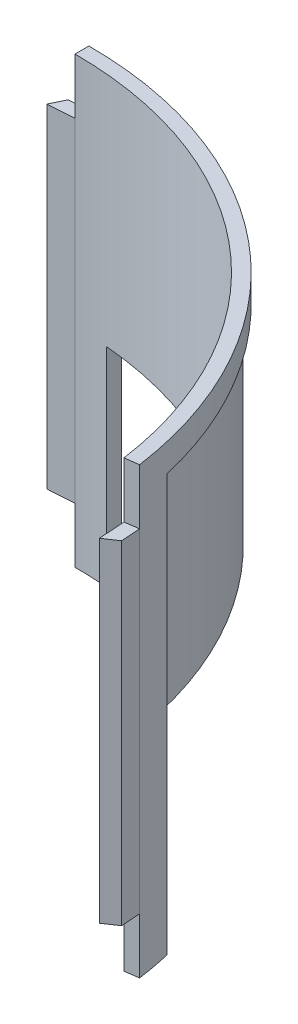
SolidWorks part; units mm, degrees
ref_plane "前视基准面" through (0, 0, 0) normal (0, 0, 1) x (1, 0, 0)
ref_plane "上视基准面" through (0, 0, 0) normal (0, 1, 0) x (1, 0, 0)
ref_plane "右视基准面" through (0, 0, 0) normal (1, 0, 0) x (0, 0, -1)
sketch "草图1" plane through (0, 0, 0) normal (0, 1, 0) x (1, 0, 0)
  line L0 (0, 705) -> (0, 0) construction
  line L1 (0, 0) -> (698.139, 98.117) construction
  line L2 (0, 705) -> (0, 680)
  line L3 (698.139, 98.117) -> (673.3823, 94.6377)
  arc A0 (0, 705) -> (698.139, 98.117) centre (0, 0) cw
  arc A1 (0, 680) -> (673.3823, 94.6377) centre (0, 0) cw
  dimension "D2" = 705
  dimension "D3" = 680
  dimension "D1" = 82
extrude "凸台-拉伸1" add sketch "草图1" along normal blind 800
ref_plane "基准面2" through (0, 400, 0) normal (0, 1, 0) x (1, 0, 0)
sketch "草图2" plane through (0, 400, 0) normal (0, 1, 0) x (1, 0, 0)
  line L0 (673.3823, 94.6377) -> (676.6911, 47.3189)
  line L2 (698.139, 98.117) -> (700.5651, 63.422)
  line L3 (676.6911, 47.3189) -> (700.5651, 63.422)
  line L4 (673.3823, 94.6377) -> (698.139, 98.117)
  line L5 (1595.1046, 111.5406) -> (1481.3826, 103.5884) construction
  dimension "D1" = 60
extrude "凸台-拉伸2" add sketch "草图2" against normal blind 300
ref_plane "基准面1" through (446.1201, 800, -513.2025) normal (-0.7547, 0, -0.6561) x (-0.6561, 0, 0.7547)
mirror "镜向1" about plane through (446.1201, 800, -513.2025) normal (-0.7547, 0, -0.6561) of "凸台-拉伸2"
mirror "镜向2" about plane through (0, 400, 0) normal (0, 1, 0) of "凸台-拉伸2"
mirror "镜向3" about plane through (446.1201, 800, -513.2025) normal (-0.7547, 0, -0.6561) of "镜向2"
sketch "草图3" plane through (0, 800, 0) normal (0, 1, 0) x (1, 0, 0)
  line L0 (0, 0) -> (462.5216, 532.0703) construction
  arc A0 (698.139, 98.117) -> (0, 705) centre (0, 0) ccw construction
ref_plane "基准面3" through (462.5216, 0, -532.0703) normal (0.6561, 0, -0.7547) x (-0.7547, 0, -0.6561)
sketch "草图4" plane through (0, 0, 0) normal (0, -1, 0) x (1, 0, 0)
  line L0 (677.2741, -155.9642) -> (687.019, -158.2083) construction
  line L1 (61.054, -702.3513) -> (60.188, -692.3889) construction
  line L2 (677.2741, -155.9642) -> (687.019, -158.2083)
  line L3 (61.054, -702.3513) -> (60.188, -692.3889)
  arc A0 (61.054, -702.3513) -> (687.019, -158.2083) centre (0, 0) ccw construction
  arc A1 (60.188, -692.3889) -> (677.2741, -155.9642) centre (0, 0) ccw construction
  arc A2 (61.054, -702.3513) -> (687.019, -158.2083) centre (0, 0) ccw
  arc A3 (60.188, -692.3889) -> (677.2741, -155.9642) centre (0, 0) ccw
extrude "切除-拉伸1" cut sketch "草图4" against normal blind 750
sketch "草图5" plane through (0, 0, 0) normal (0, -1, 0) x (1, 0, 0)
  line L0 (0, 0) -> (687.019, -158.2083) construction
  line L1 (0, 0) -> (61.054, -702.3513) construction
  line L2 (677.2741, -155.9642) -> (662.6567, -152.598)
  line L3 (60.188, -692.3889) -> (58.889, -677.4453)
  arc A0 (0, -680) -> (673.3823, -94.6377) centre (0, 0) ccw construction
  arc A1 (677.2741, -155.9642) -> (60.188, -692.3889) centre (0, 0) cw
  arc A2 (60.188, -692.3889) -> (677.2741, -155.9642) centre (0, 0) ccw construction
  arc A3 (58.889, -677.4453) -> (662.6567, -152.598) centre (0, 0) ccw
  point P20 (0, 0)
  point P21 (0, 0)
extrude "切除-拉伸2" cut sketch "草图5" against normal blind 375
